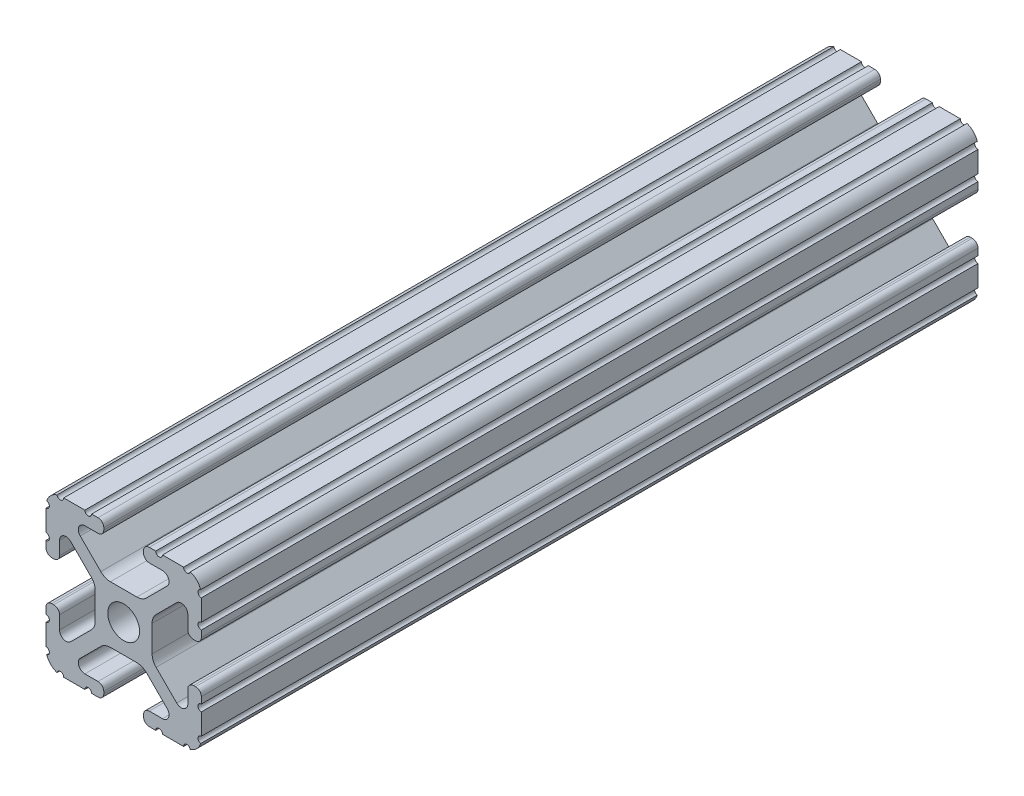
SolidWorks part; units mm, degrees
ref_plane "Front Plane" through (0, 0, 0) normal (0, 0, 1) x (1, 0, 0)
ref_plane "Top Plane" through (0, 0, 0) normal (0, 1, 0) x (1, 0, 0)
ref_plane "Right Plane" through (0, 0, 0) normal (1, 0, 0) x (0, 0, -1)
sketch "Sketch2" plane through (0, 0, 0) normal (0, 0, 1) x (1, 0, 0)
  line L0 (0, 12.7) -> (0, -12.7) construction
  line L1 (-12.7, 0) -> (12.7, 0) construction
  line L2 (3.2512, -12.7) -> (12.7, -12.7)
  line L3 (12.7, -12.7) -> (12.7, -3.2512)
  line L4 (3.2512, -12.7) -> (3.2512, -10.4902)
  line L5 (3.2512, -10.4902) -> (8.9276, -10.4902)
  line L6 (8.9276, -10.4902) -> (3.0856, -4.6482)
  line L7 (0, 0) -> (12.7, -12.7) construction
  line L8 (12.7, -3.2512) -> (10.4902, -3.2512)
  line L9 (10.4902, -3.2512) -> (10.4902, -8.9276)
  line L10 (10.4902, -8.9276) -> (4.6482, -3.0856)
  circle A0 centre (0, 0) radius 2.6035
  arc A1 (6.3485, -10.4902) -> (7.1039, -8.6665) centre (6.3485, -9.4219) ccw construction
  point P8 (0, -4.6482)
  dimension "Center Hole Diameter" = 5.207
  dimension "Rail Height" = 25.4
  dimension "Rail Width" = 25.4
  dimension "T-Slot Width" = 6.5024
  dimension "Slot Inner Width" = 14.8336
  dimension "Thickness" = 2.2098
  dimension "Slot Depth" = 5.842
  dimension "D1" = 2.2098
sketch "Sketch3" plane through (0, 0, 0) normal (1, 0, 0) x (0, 0, -1)
  line L0 (-63.5, -12.7) -> (63.5, -12.7) construction
  line L1 (-38.1, 0) -> (38.1, 0) construction
  line L3 (63.5, 0) -> (-63.5, 0) construction
  point P5 (-30.1507, -12.7)
sketch "Sketch4" plane through (0, 0, 0) normal (0, 0, 1) x (1, 0, 0)
  line L0 (4.1904, -12.7) -> (10.1173, -12.7)
  line L1 (3.2512, -12.7) -> (12.7, -12.7) construction
  line L2 (3.2512, -12.7) -> (3.2512, -10.4902) construction
  line L3 (3.2512, -10.4902) -> (8.9276, -10.4902) construction
  line L4 (3.2512, -11.4294) -> (3.2512, -11.7608)
  line L5 (4.1904, -10.4902) -> (6.3485, -10.4902)
  line L6 (0, -4.6482) -> (2.164, -4.6482)
  line L7 (8.9276, -10.4902) -> (3.0856, -4.6482) construction
  line L8 (3.7373, -5.2999) -> (7.1039, -8.6665)
  line L9 (12.7, -12.7) -> (12.7, -3.2512) construction
  line L10 (10.4902, -8.9276) -> (4.6482, -3.0856) construction
  line L11 (10.4902, -3.2512) -> (10.4902, -8.9276) construction
  line L12 (10.4902, -6.3485) -> (10.4902, -4.1904)
  line L13 (12.7, -3.2512) -> (10.4902, -3.2512) construction
  line L14 (11.4294, -3.2512) -> (11.7608, -3.2512)
  line L15 (12.7, -4.1904) -> (12.7, -10.1173)
  line L16 (8.6665, -7.1039) -> (5.2999, -3.7373)
  line L17 (4.6482, 0) -> (4.6482, -2.164)
  line L18 (-12.7, 0) -> (12.7, 0) construction
  line L19 (0, -4.6482) -> (0, -2.6035)
  line L20 (0, 12.7) -> (0, -12.7) construction
  line L21 (4.6482, 0) -> (2.6035, 0)
  arc A0 (3.2512, -11.7608) -> (4.1904, -12.7) centre (4.1904, -11.7608) ccw
  arc A2 (3.2512, -11.4294) -> (4.1904, -10.4902) centre (4.1904, -11.4294) cw
  arc A3 (6.3485, -10.4902) -> (7.1039, -8.6665) centre (6.3485, -9.4219) ccw
  arc A4 (2.164, -4.6482) -> (3.7373, -5.2999) centre (2.164, -6.8732) cw
  arc A5 (10.1173, -12.7) -> (12.7, -10.1173) centre (10.1173, -10.1173) ccw
  arc A6 (8.6665, -7.1039) -> (10.4902, -6.3485) centre (9.4219, -6.3485) ccw
  arc A7 (10.4902, -4.1904) -> (11.4294, -3.2512) centre (11.4294, -4.1904) cw
  arc A8 (11.7608, -3.2512) -> (12.7, -4.1904) centre (11.7608, -4.1904) cw
  arc A9 (5.2999, -3.7373) -> (4.6482, -2.164) centre (6.8732, -2.164) cw
  circle A10 centre (0, 0) radius 2.6035 construction
  arc A11 (0, -2.6035) -> (2.6035, 0) centre (0, 0) ccw
  dimension "D1" = 2.5827
  dimension "D2" = 2.225
  dimension "D3" = 0.9392
extrude "Boss-Extrude1" add sketch "Sketch4" along normal up to vertex (63.5 mm away) from vertex at -63.5 starting at point (0, -12.7, -63.5)
sketch "Sketch5" plane through (0, 0, 0) normal (0, 0, 1) x (1, 0, 0)
  line L0 (3.2512, -12.7) -> (12.7, -12.7) construction
  line L1 (4.1904, -10.4902) -> (6.3485, -10.4902) construction
  line L3 (0, 0) -> (12.7, -12.7) construction
  line L4 (6.3485, -10.4902) -> (6.3485, -12.7) construction
  line L5 (8.9276, -10.4902) -> (3.0856, -4.6482) construction
  circle A0 centre (10.3562, -12.7) radius 0.5524
  circle A1 centre (5.796, -12.7) radius 0.5524
  circle A2 centre (12.7, -10.3562) radius 0.5524
  circle A3 centre (12.7, -5.796) radius 0.5524
  point P10 (5.2694, -10.4902)
  point P12 (9.4219, -6.3485)
  dimension "D1" = 1.1049
extrude "Cut-Extrude1" cut sketch "Sketch5" against normal through all both and the other way through all
mirror "Mirror1" about plane through (0, 0, 0) normal (1, 0, 0) of bodies 137 134
mirror "Mirror2" about plane through (0, 0, 0) normal (0, 1, 0) of bodies 135
equation "\"D1@Sketch2\"=\"Thickness@Sketch2\""
equation "\"D2@Sketch4\"=\"Slot Inner Width@Sketch2\"*0.15"
equation "\"D1@Sketch4\"=\"D3@Sketch4\"*2.75"
equation "\"D3@Sketch4\"=\"Thickness@Sketch2\"*0.425"
equation "\"D1@Sketch5\"=\"Thickness@Sketch2\"*0.5"
equation "\"D1@Boss-Extrude1\"=\"Length@Sketch3\""
